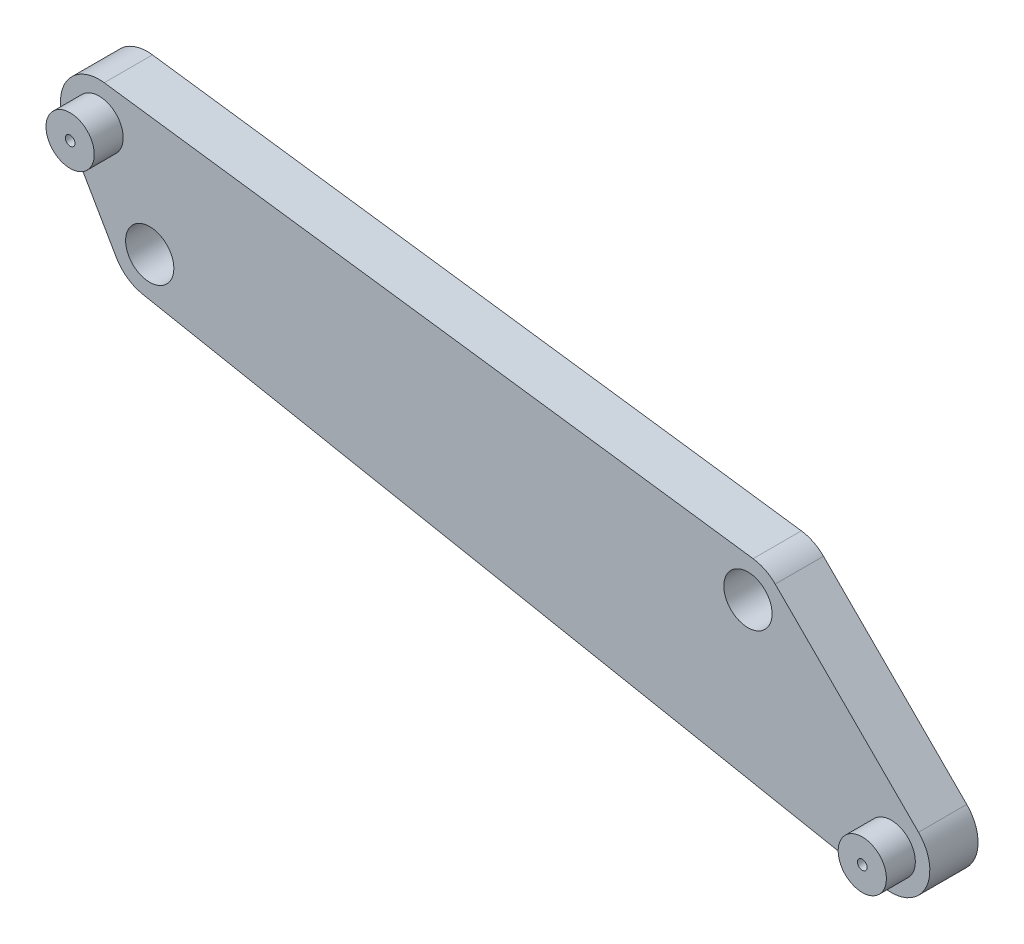
SolidWorks part; units mm, degrees
material "ABS"
ref_plane "Front Plane" through (0, 0, 0) normal (0, 0, 1) x (1, 0, 0)
ref_plane "Top Plane" through (0, 0, 0) normal (0, 1, 0) x (1, 0, 0)
ref_plane "Right Plane" through (0, 0, 0) normal (1, 0, 0) x (0, 0, -1)
sketch "Sketch1" plane through (0, 0, 0) normal (0, 0, 1) x (1, 0, 0)
  line L0 (0, 0) -> (-62, 0)
  line L1 (-62, 0) -> (-67.25, 9.0933)
  line L2 (0, 0) -> (14.8492, -14.8492)
  dimension "D1" = 62
  dimension "D2" = 10.5
  dimension "D3" = 21
  dimension "D4" = 120
  dimension "D5" = 135
sketch "Sketch2" plane through (0, 0, 0) normal (0, 0, 1) x (1, 0, 0)
  line L0 (-66.714, 13.0572) -> (0.536, 3.9639)
  line L1 (2.8284, 2.8284) -> (17.6777, -12.0208)
  line L2 (14.0904, -18.7766) -> (-62.7589, -3.9274)
  line L3 (-65.4641, -2) -> (-70.7141, 7.0933)
  circle A0 centre (-62, 0) radius 2.5
  circle A1 centre (-67.25, 9.0933) radius 2.5
  arc A2 (-66.714, 13.0572) -> (-70.7141, 7.0933) centre (-67.25, 9.0933) ccw
  arc A3 (-65.4641, -2) -> (-62.7589, -3.9274) centre (-62, 0) ccw
  circle A4 centre (0, 0) radius 2.5
  circle A5 centre (14.8492, -14.8492) radius 2.5
  arc A6 (2.8284, 2.8284) -> (0.536, 3.9639) centre (0, 0) ccw
  arc A7 (14.0904, -18.7766) -> (17.6777, -12.0208) centre (14.8492, -14.8492) ccw
  dimension "D1" = 5
  dimension "D2" = 5
  dimension "D3" = 5
  dimension "D4" = 5
  dimension "D5" = 8
  dimension "D6" = 8
  dimension "D7" = 8
  dimension "D8" = 8
extrude "Boss-Extrude1" add sketch "Sketch2" along normal blind 5
sketch "Sketch4" plane through (0, 0, 0) normal (0, 0, -1) x (-1, 0, 0)
  circle A0 centre (67.25, 9.0933) radius 2.5
  circle A1 centre (67.25, 9.0933) radius 0.5
  circle A2 centre (-14.8492, -14.8492) radius 2.5
  circle A3 centre (-14.8492, -14.8492) radius 0.5
  dimension "D1" = 1
  dimension "D2" = 5
  dimension "D3" = 5
  dimension "D4" = 1
extrude "Boss-Extrude3" add sketch "Sketch4" against normal blind 8
